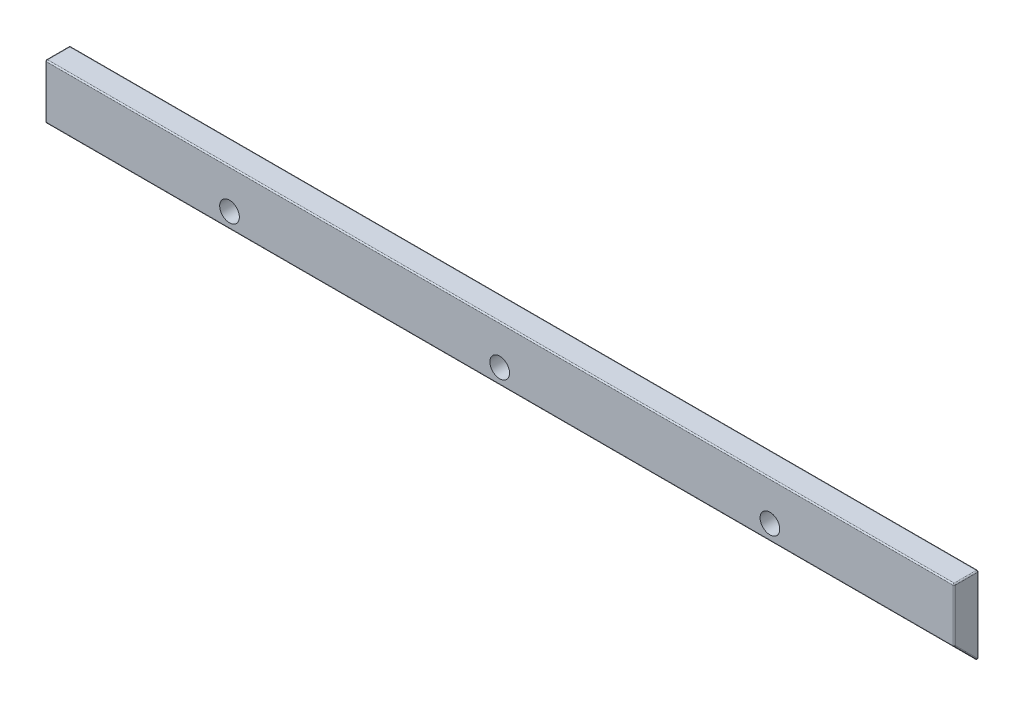
SolidWorks part; units mm, degrees
material "6061-T6 (SS)"
ref_plane "Front Plane" through (0, 0, 0) normal (0, 0, 1) x (1, 0, 0)
ref_plane "Top Plane" through (0, 0, 0) normal (0, 1, 0) x (1, 0, 0)
ref_plane "Right Plane" through (0, 0, 0) normal (1, 0, 0) x (0, 0, -1)
sketch "Sketch1" plane through (0, 0, 0) normal (1, 0, 0) x (0, 0, -1)
  line L0 (-3.0983, 0) -> (1.226, 0) construction
  line L1 (0, -3.2) -> (-2, -1.2)
  line L2 (0, -3.2) -> (0, 3.2)
  line L4 (-2, -1.2) -> (-2, 3.2)
  line L5 (-2, 3.2) -> (0, 3.2)
  line L6 (-2, -1.2) -> (0, -3.2) construction
  dimension "D1" = 2
extrude "Boss-Extrude1" add sketch "Sketch1" along normal up to surface (37 mm away) and the other way up to surface (37 mm away)
fillet "Fillet1" radius 0.1 12 edges at (0, 3.2, 0) (0, 3.2, 2) (0, -3.2, 0) (0, -1.2, 2) (37, 1, 2) (37, 3.2, 1) (37, 0, 0) (37, -2.2, 1) (-37, 3.2, 1) (-37, 1, 2) (-37, -2.2, 1) (-37, 0, 0)
sketch "Sketch4" [suppressed] plane through (0, 0, 0) normal (0, 0, 1) x (1, 0, 0)
  line L1 (7.5, 1.5) -> (-7.5, 1.5)
  line L2 (7.5, 1.5) -> (7.5, -3.2)
  line L3 (7.5, -3.2) -> (-7.5, -3.2)
  line L4 (-7.5, 1.5) -> (-7.5, -3.2)
  line L5 (0, 7.7759) -> (0, -8.8374) construction
  line L8 (-7.5, -3.2) -> (-7.5, 0.8) construction
  dimension "D1" = 4.7
hole_wizard "M2x0.4 Tapped Hole1" positions "Sketch2" profile "Sketch3" tap size "M2x0.4" standard "ANSI Metric" end condition through all
sketch "Sketch2" plane through (0, 0, 2) normal (0, 0, 1) x (1, 0, 0)
  circle A0 centre (-22, 0) radius 1.2
  circle A1 centre (-22, 0) radius 1.2 construction
  circle A2 centre (22, 0) radius 1.2
  circle A3 centre (22, 0) radius 1.2 construction
  point P0 (22, 0)
  point P2 (0, 0)
  point P5 (-22, 0)
sketch "Sketch3" plane through (22, 0, 2) normal (1, 0, 0) x (0, -1, 0)
  line L0 (0, 0) -> (0, 2)
  line L1 (0, 2) -> (0.8, 2)
  line L2 (0.8, 2) -> (0.8, 0)
  line L5 (0.8, 0) -> (0, 0)
  line L11 (0, -6.35) -> (0, 107.95) construction
  dimension "Thru Tap Drill Dia." = 1.6
  dimension "Thru Tap Drill Depth" = 2
cosmetic thread "Hole Thread1" parameters "D2"=2
cosmetic thread "Hole Thread2" parameters "D2"=2
cosmetic thread "Hole Thread3" parameters "D2"=2
extrude "Cut-Extrude4" [suppressed] cut sketch "Sketch4" along normal through all
fillet "Fillet2" [suppressed] radius 0.2
